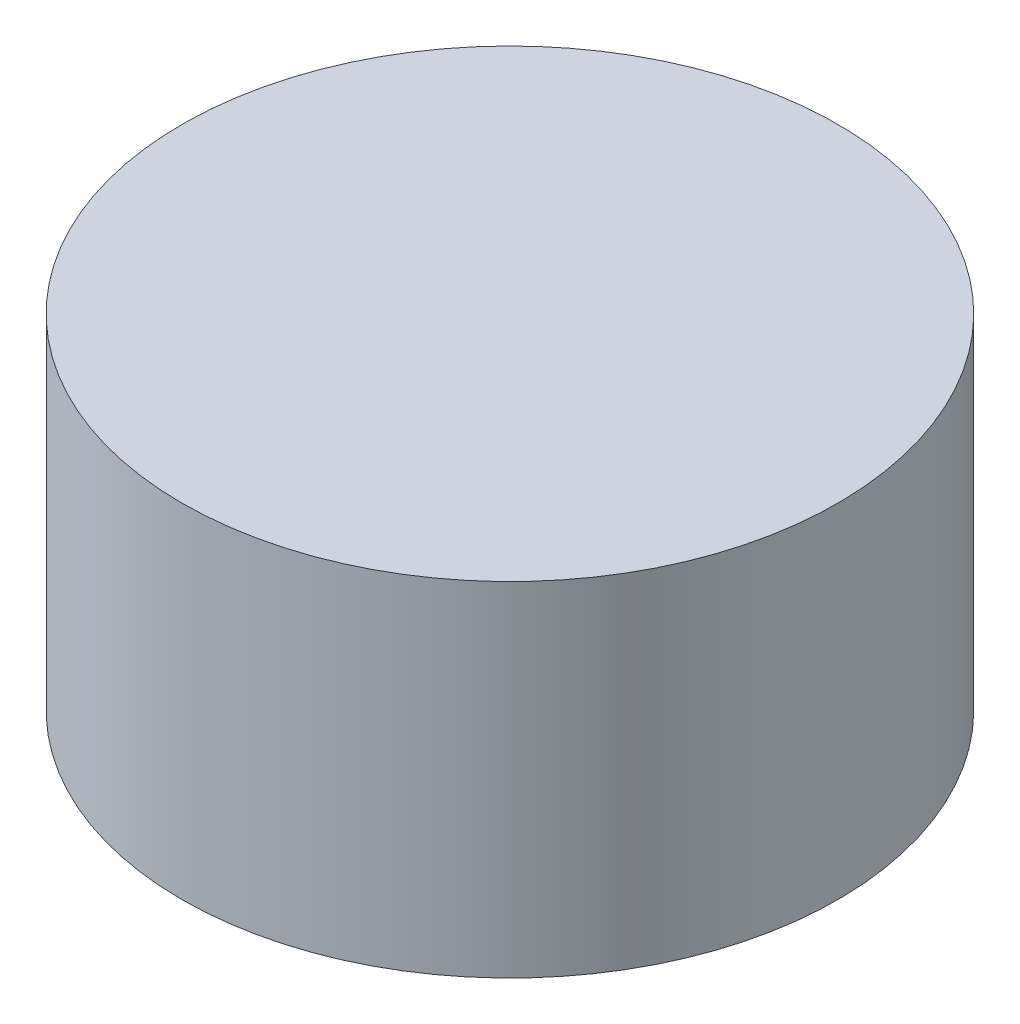
SolidWorks part; units mm, degrees
material "6061 Alloy"
ref_plane "Front Plane" through (0, 0, 0) normal (0, 0, 1) x (1, 0, 0)
ref_plane "Top Plane" through (0, 0, 0) normal (0, 1, 0) x (1, 0, 0)
ref_plane "Right Plane" through (0, 0, 0) normal (1, 0, 0) x (0, 0, -1)
sketch "Sketch1" plane through (0, 0, 0) normal (0, 1, 0) x (1, 0, 0)
  circle A0 centre (0, 0) radius 24.2594
extrude "Boss-Extrude1" add sketch "Sketch1" along normal blind 25.4
